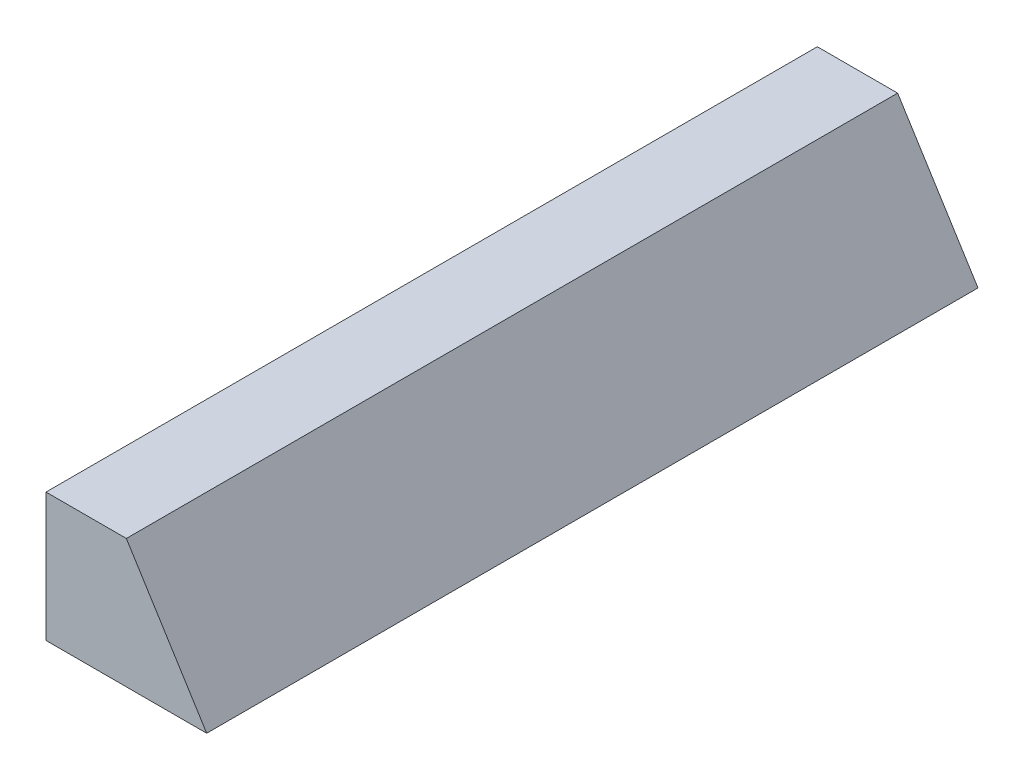
SolidWorks part; units mm, degrees
ref_plane "Front Plane" through (0, 0, 0) normal (0, 0, 1) x (1, 0, 0)
ref_plane "Top Plane" through (0, 0, 0) normal (0, 1, 0) x (1, 0, 0)
ref_plane "Right Plane" through (0, 0, 0) normal (1, 0, 0) x (0, 0, -1)
sketch "Sketch2" plane through (0, 0, 0) normal (0, 0, 1) x (1, 0, 0)
  line L0 (-52.0655, 37.313) -> (-52.0655, 88.113)
  line L2 (-52.0655, 37.313) -> (-52.0655, -13.487)
  line L3 (-52.0655, -13.487) -> (74.9345, -13.487)
  line L5 (-52.0655, 88.113) -> (11.4345, 88.113)
  line L6 (74.9345, -13.487) -> (11.4345, 88.113)
  line L7 (11.4345, 88.113) -> (74.9345, -13.487)
  point P6 (73.8392, -26.7559)
  dimension "D1" = 127
  dimension "D2" = 50.8
  dimension "D3" = 50.8
  dimension "D4" = 63.5
extrude "Boss-Extrude1" add sketch "Sketch2" along normal blind 609.6 contours L3 L6 L5 L0 L2
shell "Shell2" thickness 2.54
